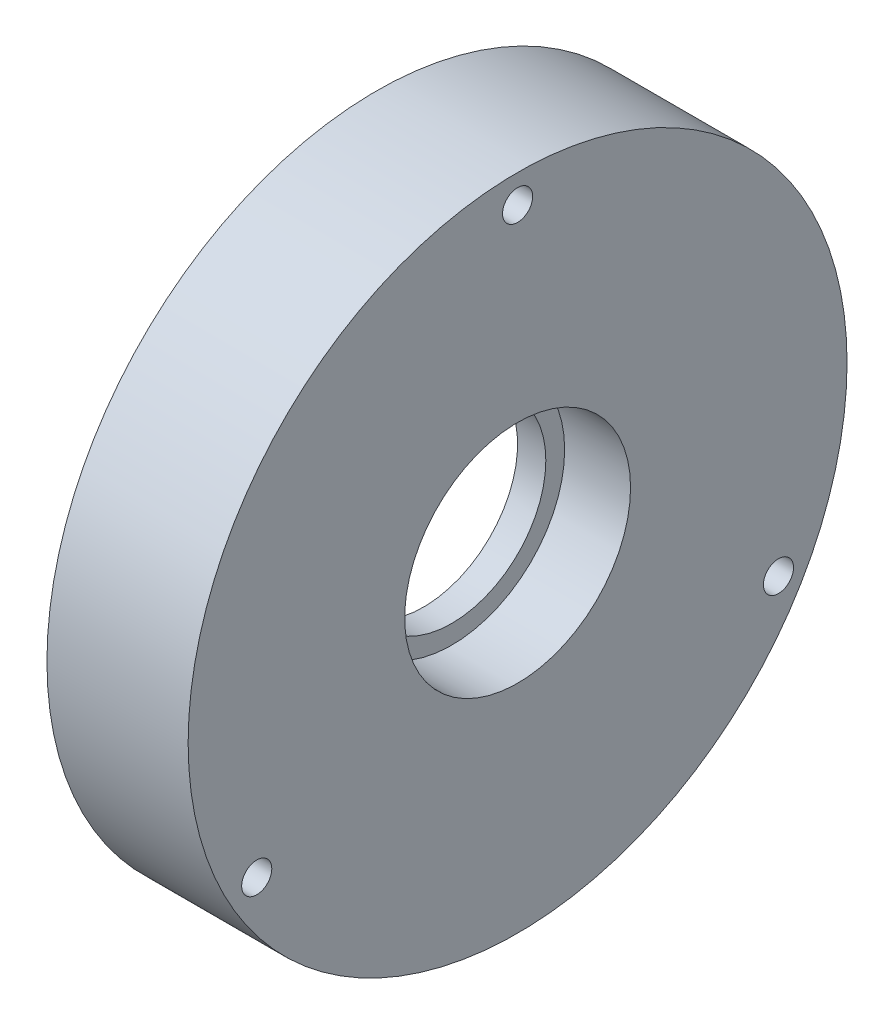
SolidWorks part; units mm, degrees
ref_plane "Plane1" through (0, 0, 0) normal (0, 0, 1) x (1, 0, 0)
ref_plane "Plane2" through (0, 0, 0) normal (0, 1, 0) x (1, 0, 0)
ref_plane "Plane3" through (0, 0, 0) normal (1, 0, 0) x (0, 0, -1)
sketch "HoldingSke" plane through (0, 0, 0) normal (0, 1, 0) x (1, 0, 0)
  line L0 (0, 0) -> (1.1472, -1.6383)
  line L1 (-15, 0) -> (100, 0) construction
  line L2 (0, 0) -> (-2.1039, 2.3779)
  line L3 (0, 0) -> (-11.863, 4.5341)
  line L4 (0, 0) -> (4.9534, 7.0742)
  line L5 (0, 0) -> (-23.7986, -8.8762)
  line L6 (0, 0) -> (-10.5278, -7.1032)
  line L7 (-2.1039, 2.3779) -> (3.3635, 27.1825)
  line L8 (-76.2, 2.8779) -> (-54.61, 2.8779)
  line L9 (-71.009, 38.7566) -> (-53.1078, 45.2721)
  line L10 (-76.2, 71.12) -> (104.1128, 71.12)
  line L11 (0, 0) -> (-5, 0)
  line L12 (-76.2, 101.6) -> (-76.181, 101.6)
  line L13 (24.9733, 27.94) -> (52.9518, 28.4284)
  line L14 (24.9733, 27.94) -> (24.9743, 27.94)
  line L15 (24.9733, 27.94) -> (100.4006, 29.5858)
  circle A0 centre (0, 0) radius 17.5
  circle A1 centre (0, 0) radius 12.7
  circle A2 centre (0, 0) radius 12.7
  dimension "MHD" = 25.4
  dimension "Hub_dia" = 25.4
  dimension "Diameter" = 35
  dimension "Num_teeth" = 55
  dimension "Pitch" = 2
  dimension "Overall_len" = 25.4
  dimension "Show_teeth" = 55
  dimension "Thickness" = 12.7
  dimension "OAL" = 25.4001
  dimension "T_dim" = 21.59
  dimension "Ap" = 20
  dimension "H" = 19.05
  dimension "Pitch_radius" = 180.3128
  dimension "Width" = 5
  dimension "Backlash" = 0.019
  dimension "Addendum_fac" = 1
  dimension "Dedendum_fac" = 1.25
  dimension "Clearance_fac" = 0.25
  dimension "Dedendum_add" = 0.001
  dimension "Module" = 0.5
sketch "BasProSke" plane through (0, 0, 0) normal (0, 1, 0) x (1, 0, 0)
  line L0 (-10, 0) -> (60, 0) construction
  line L1 (0, 13.25) -> (0, 17.5)
  line L2 (0, 13.25) -> (5, 13.25)
  line L3 (5, 13.25) -> (5, 17.5)
  line L4 (5, 17.5) -> (0, 17.5)
  dimension "Diameter" = 35
  dimension "Thickness" = 5
  dimension "Inside_diameter" = 26.5
revolve "Base-Revolve" add sketch "BasProSke" angle 360 about L0
sketch "TooCutSke" plane through (0, 0, 0) normal (1, 0, 0) x (0, 0, -1)
  line L3 (0.4401, 13.743) -> (0.4401, 53.6633) construction
  line L4 (0, 0) -> (0, 59.563) construction
  line L5 (0, 0) -> (-3.9007, 68.2161) construction
  line L6 (-5.9882, 11.3053) -> (37.1172, 13.7701) construction
  circle A0 centre (0, 0) radius 13.75 construction
  circle A1 centre (0, 0) radius 14.376 construction
  circle A2 centre (0, 0) radius 11.6287 construction
  circle A3 centre (0, 0) radius 13.2246 construction
  arc A4 (0.6177, 13.2102) -> (0.1634, 14.3751) centre (-5.9882, 11.3053) ccw
  arc A5 (0.6177, 13.2102) -> (-0.6177, 13.2102) centre (0, 0) ccw
  arc A6 (0.1634, 14.3751) -> (-0.1634, 14.3751) centre (0, 0) ccw
  arc A7 (-0.1634, 14.3751) -> (-0.6177, 13.2102) centre (5.9882, 11.3053) ccw
  dimension "Pitch_dia" = 27.5
  dimension "Base_dia" = 23.2574
  dimension "Root_dia" = 28.752
  dimension "Overcut_dia" = 26.4492
  dimension "Flank_rad" = 6.875
  dimension "Half_ang" = 3.273
  dimension "Half_CT" = 0.4401
extrude "ToothCut" cut sketch "TooCutSke" along normal through all
fillet "Breaks" [suppressed] radius 0.05
fillet "RootFillets" [suppressed] radius 0.126
pattern_circular "TeethCuts" count 55 every 6.545 about axis through (-10, 0, 0) along (1, 0, 0) of "RootFillets", "Breaks", "ToothCut"
sketch "Sketch1" plane through (5, 0, 0) normal (1, 0, 0) x (0, 0, -1)
  circle A0 centre (0, 0) radius 17.5
  circle A1 centre (0, 0) radius 5
  dimension "D1" = 10
extrude "Boss-Extrude1" add sketch "Sketch1" along normal blind 2.5
sketch "Sketch2" plane through (5, 0, 0) normal (-1, 0, 0) x (0, 0, 1)
  circle A0 centre (0, 0) radius 5
  circle A1 centre (0, 0) radius 7.75
  dimension "D1" = 10
  dimension "D2" = 15.5
extrude "Boss-Extrude2" add sketch "Sketch2" along normal blind 2.5
sketch "Sketch3" plane through (7.5, 0, 0) normal (1, 0, 0) x (0, 0, -1)
  circle A0 centre (0, 0) radius 6
  dimension "D1" = 12
extrude "Cut-Extrude1" cut sketch "Sketch3" against normal blind 3.5
hole_wizard "M2 Tapped Hole1" positions "Sketch5" profile "Sketch6" tap size "M2" standard "ISO"
sketch "Sketch5" plane through (7.5, 0, 0) normal (1, 0, 0) x (0, 0, -1)
  line L2 (0, 19.3966) -> (0, 0) construction
  point P0 (0, 16)
  dimension "D1" = 16
sketch "Sketch6" plane through (7.5, 16, 0) normal (0, 1, 0) x (0, 0, -1)
  line L0 (0, 0) -> (0, 5.6807)
  line L1 (0, 5.6807) -> (0.8, 5.2)
  line L2 (0.8, 5.2) -> (0.8, 0)
  line L5 (0.8, 0) -> (0, 0)
  line L10 (0, 5.6807) -> (-0.8, 5.2) construction
  line L11 (0, -6.35) -> (0, 107.95) construction
  dimension "Tap Drill Dia." = 1.6
  dimension "Tap Drill Depth" = 5.2
  dimension "Drill Angle" = 118
cosmetic thread "Hole Thread1" parameters "D1"=4, "D2"=2
pattern_circular "CirPattern1" count 3 over 360 about axis through (0, 0, 0) along (1, 0, 0) of "M2 Tapped Hole1"
equation "' \"Module@HoldingSke\" = 6.35"
equation "' \"Num_teeth@HoldingSke\" = 24"
equation "' \"Ap@HoldingSke\" =  14.5"
equation "' \"Ap@HoldingSke\" = 14.5"
equation "' \"Width@HoldingSke\" = 12"
equation "' \"Diameter@HoldingSke\" = 8 * 25.4"
equation "' \"Show_teeth@HoldingSke\" = 100"
equation "' \"Backlash@HoldingSke\" = 0.009 * 25.4"
equation "' \"Addendum_fac@HoldingSke\" = 1.0"
equation "' \"Dedendum_fac@HoldingSke\" = 1.25"
equation "' \"Dedendum_add@HoldingSke\" = 0.00005 * 25.4"
equation "' \"Clearance_fac@HoldingSke\" = 0.25"
equation "\"Pitch@HoldingSke\" = 1 / \"Module@HoldingSke\" "
equation "\"Overcut_dia@TooCutSke\" = (\"Num_teeth@HoldingSke\" - 2 * \"Addendum_fac@HoldingSke\") / \"Pitch@HoldingSke\" - 0.002 * 25.4"
equation "\"Pitch_dia@TooCutSke\" = \"Num_teeth@HoldingSke\" / \"Pitch@HoldingSke\""
equation "\"Base_dia@TooCutSke\" = \"Num_teeth@HoldingSke\" / \"Pitch@HoldingSke\" * cos((\"Ap@HoldingSke\"  * 3.14159265 / 180)) * 0.90"
equation "\"Root_dia@TooCutSke\" = \"Num_teeth@HoldingSke\"  / \"Pitch@HoldingSke\" + 2 *  \"Dedendum_fac@HoldingSke\"/ \"Pitch@HoldingSke\" + \"Dedendum_add@HoldingSke\" * 2"
equation "\"Half_ang@TooCutSke\" = 180 / \"Num_teeth@HoldingSke\""
equation "\"Half_CT@TooCutSke\" = \"Num_teeth@HoldingSke\" / \"Pitch@HoldingSke\" * sin((3.14159265 / 2 / \"Num_teeth@HoldingSke\")) / 2 + 10 * \"Backlash@HoldingSke\" / 4"
equation "\"Flank_rad@TooCutSke\" = \"Num_teeth@HoldingSke\" / \"Pitch@HoldingSke\" / 4"
equation "\"Radius@RootFillets\"= \"Clearance_fac@HoldingSke\" / \"Pitch@HoldingSke\" + \"Dedendum_add@HoldingSke\""
equation "\"Break_rad@Breaks\" = 0.02 / \"Pitch@HoldingSke\" * 5"
equation "\"Num_teeth@TeethCuts\" = int( \"Show_teeth@HoldingSke\" ) + 1"
equation "\"Num_teeth@TeethCuts\" = ((sgn( \"Num_teeth@TeethCuts\" - \"Num_teeth@HoldingSke\" )-1)*( \"Num_teeth@TeethCuts\" - \"Num_teeth@HoldingSke\" ))/-2+ \"Num_teeth@HoldingSke\""
equation "\"Num_teeth@TeethCuts\" = ((sgn( \"Num_teeth@TeethCuts\" - 2.0)+1)*( \"Num_teeth@TeethCuts\" - 2.0))/2 +2.0"
equation "\"Angle@TeethCuts\" = 360.0 / \"Num_teeth@HoldingSke\""
equation "\"Diameter@BasProSke\" = \"Num_teeth@HoldingSke\"  / \"Pitch@HoldingSke\" + 2 *  \"Dedendum_fac@HoldingSke\"/ \"Pitch@HoldingSke\" + \"Dedendum_add@HoldingSke\" * 2 + 0.002 * 25.4"
equation "\"Diameter@BasProSke\" = ((sgn( \"Diameter@BasProSke\"  - \"Diameter@HoldingSke\" )+1)*( \"Diameter@BasProSke\"  - \"Diameter@HoldingSke\" ))/2 + \"Diameter@HoldingSke\""
equation "\"Inside_diameter@BasProSke\" =  (\"Num_teeth@HoldingSke\" - 2 * \"Addendum_fac@HoldingSke\") / \"Pitch@HoldingSke\" "
equation "\"Thickness@BasProSke\"  = \"Width@HoldingSke\""
